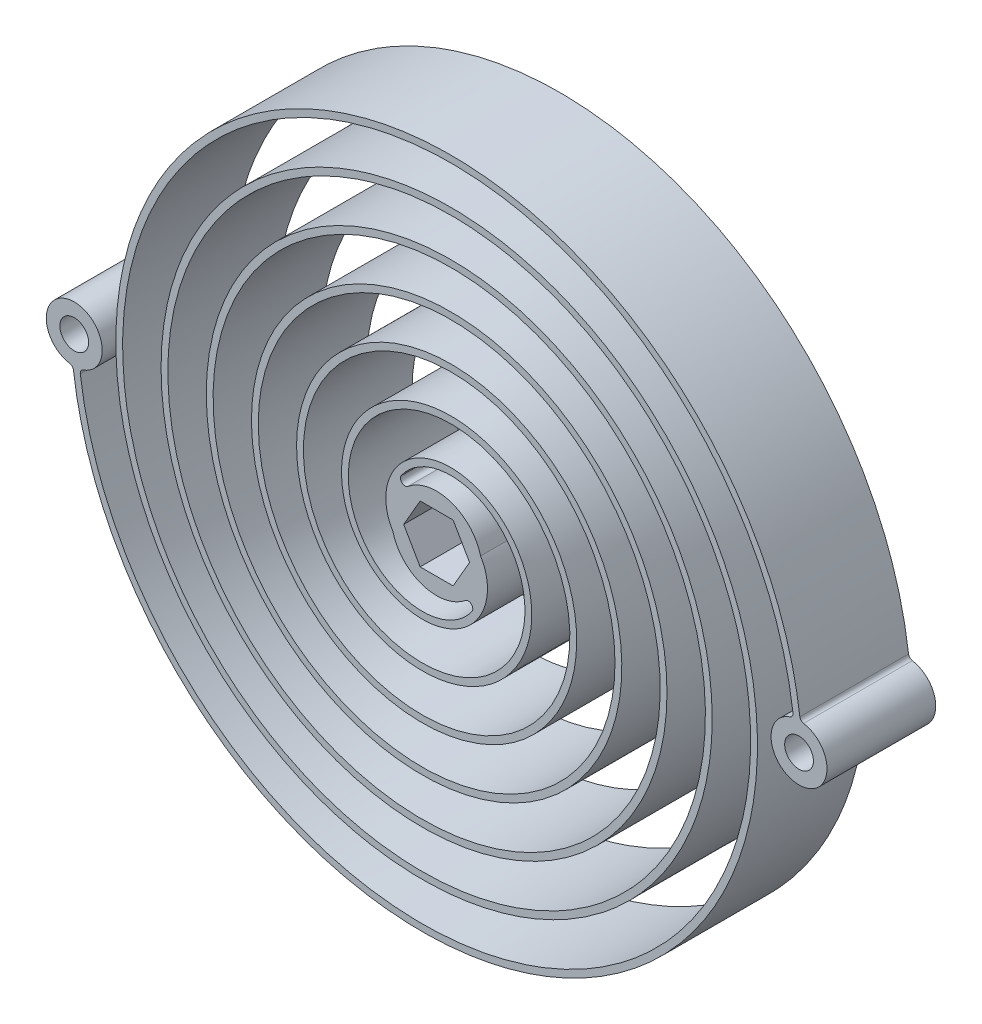
SolidWorks part; units mm, degrees
material "ASTM A36 Steel"
ref_plane "Front Plane" through (0, 0, 0) normal (0, 0, 1) x (1, 0, 0)
ref_plane "Top Plane" through (0, 0, 0) normal (0, 1, 0) x (1, 0, 0)
ref_plane "Right Plane" through (0, 0, 0) normal (1, 0, 0) x (0, 0, -1)
sketch "Base Spring Geometry" plane through (0, 0, 0) normal (0, 0, 1) x (1, 0, 0)
  line L1 (1.8187, 3.15) -> (-1.8187, 3.15)
  line L2 (-1.8187, 3.15) -> (-3.6373, 0)
  line L3 (-3.6373, 0) -> (-1.8187, -3.15)
  line L4 (-1.8187, -3.15) -> (1.8187, -3.15)
  line L5 (1.8187, -3.15) -> (3.6373, 0)
  line L6 (3.6373, 0) -> (1.8187, 3.15)
  circle A1 centre (0, 0) radius 40 construction
  circle A3 centre (0, 0) radius 5
  circle A4 centre (0, 0) radius 3.15 construction
  point P26 (0, 0)
  dimension "D1" = 6.3
sketch "Spring Spiral" plane through (0, 0, 0) normal (0, 0, 1) x (1, 0, 0)
  circle A0 centre (0, 0) radius 5
  dimension "D1" = 10
curve "Spring Arm Spiral"
sketch "Sketch12" plane through (0, 0, 0) normal (0, 0, 1) x (1, 0, 0)
  line L1 (3.6373, 0) -> (1.8187, 3.15)
  line L2 (1.8187, 3.15) -> (-1.8187, 3.15)
  line L3 (-1.8187, 3.15) -> (-3.6373, 0)
  line L4 (-3.6373, 0) -> (-1.8187, -3.15)
  line L5 (-1.8187, -3.15) -> (1.8187, -3.15)
  line L6 (1.8187, -3.15) -> (3.6373, 0)
  circle A1 centre (0, 0) radius 5
  circle A2 centre (0, 0) radius 5 construction
  circle A3 centre (0, 0) radius 3.15 construction
  point P5 (3.6373, 0)
extrude "Boss-Extrude2" add sketch "Sketch12" along normal blind 12
sketch "Sketch11" plane through (0, 0, 0) normal (0, 0, 1) x (1, 0, 0)
  arc A0 (4.8487, -1.2209) -> (4.8501, 1.2153) centre (0, 0) ccw
  circle A2 centre (0, 0) radius 5 construction
  circle A6 centre (-40, 0) radius 1.5875
  circle A7 centre (0, 0) radius 40 construction
  arc A8 (-39.3865, -3.0259) -> (-40.1348, -3.0846) centre (-40, 0) ccw
  spline S2 degree 3 poles (737.1809, -1858.5171) (-139.9817, 13.4916) (6.25, 19.9602) (4.809, -2.4575) (4.6525, -3.0957) (4.0874, -4.3221) (3.6775, -4.9127) (2.6256, -5.9433) (1.9815, -6.385) (0.521, -7.0272) (-0.2978, -7.2284) (-2.0136, -7.3241) (-2.9131, -7.2183) (-4.6721, -6.6722) (-5.5338, -6.2309) (-7.0911, -5.032) (-7.7882, -4.2727) (-8.8994, -2.5037) (-9.3144, -1.4919) (-9.7717, 0.6732) (-9.8141, 1.8288) (-9.4796, 4.1416) (-9.1019, 5.301) (-7.9336, 7.467) (-7.1417, 8.4754) (-5.2081, 10.1914) (-4.0646, 10.9001) (-1.5445, 11.8953) (-0.1658, 12.1823) (2.6671, 12.2586) (4.1232, 12.0476) (6.9297, 11.1119) (8.2818, 10.3862) (10.6978, 8.4714) (11.7632, 7.2808) (13.4469, 4.5509) (14.066, 3.0097) (14.7442, -0.2525) (14.8035, -1.9756) (14.3129, -5.3972) (13.7626, -7.0977) (12.0786, -10.2585) (10.9438, -11.7202) (8.193, -14.2038) (6.5754, -15.2266) (3.0289, -16.6749) (1.0982, -17.1008) (-2.8541, -17.2637) (-4.8775, -17.0005) (-8.7695, -15.7747) (-10.6397, -14.8114) (-13.9842, -12.2621) (-15.4597, -10.6749) (-17.8092, -7.0375) (-18.6837, -4.9857) (-19.689, -0.6455) (-19.8198, 1.6445) (-19.2799, 6.1926) (-18.6087, 8.4522) (-16.5039, 12.6601) (-15.0693, 14.6096) (-11.5732, 17.942) (-9.5104, 19.3257) (-4.9781, 21.3279) (-2.5071, 21.9467) (2.5601, 22.3051) (5.1577, 22.0445) (10.1674, 20.6329) (12.5807, 19.4811) (16.919, 16.3849) (18.8448, 14.4393) (21.9509, 9.9551) (23.1316, 7.4153) (24.57, 2.024) (24.8277, -0.8287) (24.3475, -6.5134) (23.6092, -9.3466) (21.1829, -14.6477) (19.4943, -17.1166) (15.3312, -21.3748) (12.8561, -23.1644) (8.7533, -25.1557) (7.3211, -25.7047) (4.3686, -26.552) (2.848, -26.8502) (-0.2371, -27.1818) (-1.802, -27.2151) (-4.9295, -27.0105) (-6.4924, -26.7726) (-9.5688, -26.0273) (-11.0827, -25.5199) (-14.0144, -24.2455) (-15.4325, -23.4785) (-18.1284, -21.7031) (-19.4064, -20.6945) (-21.7806, -18.4616) (-22.8771, -17.2371) (-24.8521, -14.6052) (-25.7308, -13.1975) (-27.2394, -10.2381) (-27.8696, -8.6861) (-28.8577, -5.4819) (-29.2158, -3.8295) (-29.6439, -0.4723) (-29.714, 1.2327) (-29.5588, 4.6449) (-29.3335, 6.3522) (-28.589, 9.7178) (-28.0696, 11.3762) (-26.7473, 14.5932) (-25.9441, 16.152) (-24.0732, 19.1212) (-23.0053, 20.5319) (-20.6322, 23.1597) (-19.3268, 24.377) (-16.5138, 26.5785) (-15.006, 27.5627) (-11.8297, 29.2642) (-10.161, 29.9817) (-6.7105, 31.1235) (-4.9283, 31.548) (-1.3021, 32.0862) (0.5421, 32.1999) (4.2382, 32.1079) (6.0902, 31.9022) (9.7465, 31.1722) (11.551, 30.6477) (15.0572, 29.2906) (16.7593, 28.4579) (20.0079, 26.5039) (21.5548, 25.3826) (24.4443, 22.8805) (25.7872, 21.4995) (28.225, 18.515) (29.3202, 16.9114) (31.2261, 13.5261) (32.0368, 11.7442) (33.345, 8.053) (33.8424, 6.1434) (34.5041, 2.2518) (34.6683, 0.2696) (34.6534, -3.7092) (34.4743, -5.7059) (33.7725, -9.654) (33.2499, -11.6057) (31.8715, -15.4047) (31.0157, -17.2522) (28.9914, -20.7861) (27.8228, -22.4727) (25.2031, -25.6317) (23.7518, -27.1043) (20.606, -29.7882) (18.9112, -30.9996) (15.3252, -33.121) (13.4338, -34.031) (9.5081, -35.5179) (7.4737, -36.0948) (3.3207, -36.8933) (1.2019, -37.1148) (-3.0578, -37.1908) (-5.1989, -37.0452) (-9.4396, -36.3856) (-11.5394, -35.8717) (-15.6341, -34.4857) (-17.6292, -33.6135) (-21.4535, -31.5317) (-23.2829, -30.322) (-26.7188, -27.5966) (-28.3254, -26.0807) (-31.2646, -22.7839) (-32.5974, -21.0027) (-34.9451, -17.2246) (-35.9602, -15.2275) (-37.6381, -11.0742) (-38.3009, -8.9178) (-57.4366, 80.0549) (215.829, 242.2912) (1201.7751, -1542.9243) knots -0.540256 -0.540256 -0.540256 -0.540256 0.015625 0.015625 0.03125 0.03125 0.046875 0.046875 0.0625 0.0625 0.078125 0.078125 0.09375 0.09375 0.109375 0.109375 0.125 0.125 0.140625 0.140625 0.15625 0.15625 0.171875 0.171875 0.1875 0.1875 0.203125 0.203125 0.21875 0.21875 0.234375 0.234375 0.25 0.25 0.265625 0.265625 0.28125 0.28125 0.296875 0.296875 0.3125 0.3125 0.328125 0.328125 0.34375 0.34375 0.359375 0.359375 0.375 0.375 0.390625 0.390625 0.40625 0.40625 0.421875 0.421875 0.4375 0.4375 0.453125 0.453125 0.46875 0.46875 0.484375 0.484375 0.5 0.5 0.515625 0.515625 0.53125 0.53125 0.546875 0.546875 0.5625 0.5625 0.578125 0.578125 0.59375 0.59375 0.609375 0.609375 0.625 0.625 0.632812 0.632812 0.640625 0.640625 0.648437 0.648437 0.65625 0.65625 0.664062 0.664062 0.671875 0.671875 0.679687 0.679687 0.6875 0.6875 0.695312 0.695312 0.703125 0.703125 0.710937 0.710937 0.71875 0.71875 0.726562 0.726562 0.734375 0.734375 0.742187 0.742187 0.75 0.75 0.757812 0.757812 0.765625 0.765625 0.773438 0.773438 0.78125 0.78125 0.789062 0.789062 0.796875 0.796875 0.804688 0.804688 0.8125 0.8125 0.820312 0.820312 0.828125 0.828125 0.835938 0.835938 0.84375 0.84375 0.851562 0.851562 0.859375 0.859375 0.867188 0.867188 0.875 0.875 0.882812 0.882812 0.890625 0.890625 0.898438 0.898438 0.90625 0.90625 0.914062 0.914062 0.921875 0.921875 0.929688 0.929688 0.9375 0.9375 0.945312 0.945312 0.953125 0.953125 0.960938 0.960938 0.96875 0.96875 0.976562 0.976562 0.984375 0.984375 0.992188 0.992188 1.299623 1.299623 1.299623 1.299623 only from (4.6427, -0.1137) to (-29.6436, 0.4118)
  spline S3 degree 3 poles (4.8487, -1.2209) (4.8617, -1.425) (4.862, -1.6335) (4.809, -2.4575) (4.6525, -3.0957) (4.0874, -4.3221) (3.6775, -4.9127) (2.6256, -5.9433) (1.9815, -6.385) (0.521, -7.0272) (-0.2978, -7.2284) (-2.0136, -7.3241) (-2.9131, -7.2183) (-4.6721, -6.6722) (-5.5338, -6.2309) (-7.0911, -5.032) (-7.7882, -4.2727) (-8.8994, -2.5037) (-9.3144, -1.4919) (-9.7717, 0.6732) (-9.8141, 1.8288) (-9.4796, 4.1416) (-9.1019, 5.301) (-7.9336, 7.467) (-7.1417, 8.4754) (-5.2081, 10.1914) (-4.0646, 10.9001) (-1.5445, 11.8953) (-0.1658, 12.1823) (2.6671, 12.2586) (4.1232, 12.0476) (6.9297, 11.1119) (8.2818, 10.3862) (10.6978, 8.4714) (11.7632, 7.2808) (13.4469, 4.5509) (14.066, 3.0097) (14.7442, -0.2525) (14.8035, -1.9756) (14.3129, -5.3972) (13.7626, -7.0977) (12.0786, -10.2585) (10.9438, -11.7202) (8.193, -14.2038) (6.5754, -15.2266) (3.0289, -16.6749) (1.0982, -17.1008) (-2.8541, -17.2637) (-4.8775, -17.0005) (-8.7695, -15.7747) (-10.6397, -14.8114) (-13.9842, -12.2621) (-15.4597, -10.6749) (-17.8092, -7.0375) (-18.6837, -4.9857) (-19.689, -0.6455) (-19.8198, 1.6445) (-19.2799, 6.1926) (-18.6087, 8.4522) (-16.5039, 12.6601) (-15.0693, 14.6096) (-11.5732, 17.942) (-9.5104, 19.3257) (-4.9781, 21.3279) (-2.5071, 21.9467) (2.5601, 22.3051) (5.1577, 22.0445) (10.1674, 20.6329) (12.5807, 19.4811) (16.919, 16.3849) (18.8448, 14.4393) (21.9509, 9.9551) (23.1316, 7.4153) (24.57, 2.024) (24.8277, -0.8287) (24.3475, -6.5134) (23.6092, -9.3466) (21.1829, -14.6477) (19.4943, -17.1166) (15.3312, -21.3748) (12.8561, -23.1644) (8.7533, -25.1557) (7.3211, -25.7047) (4.3686, -26.552) (2.848, -26.8502) (-0.2371, -27.1818) (-1.802, -27.2151) (-4.9295, -27.0105) (-6.4924, -26.7726) (-9.5688, -26.0273) (-11.0827, -25.5199) (-14.0144, -24.2455) (-15.4325, -23.4785) (-18.1284, -21.7031) (-19.4064, -20.6945) (-21.7806, -18.4616) (-22.8771, -17.2371) (-24.8521, -14.6052) (-25.7308, -13.1975) (-27.2394, -10.2381) (-27.8696, -8.6861) (-28.8577, -5.4819) (-29.2158, -3.8295) (-29.6439, -0.4723) (-29.714, 1.2327) (-29.5588, 4.6449) (-29.3335, 6.3522) (-28.589, 9.7178) (-28.0696, 11.3762) (-26.7473, 14.5932) (-25.9441, 16.152) (-24.0732, 19.1212) (-23.0053, 20.5319) (-20.6322, 23.1597) (-19.3268, 24.377) (-16.5138, 26.5785) (-15.006, 27.5627) (-11.8297, 29.2642) (-10.161, 29.9817) (-6.7105, 31.1235) (-4.9283, 31.548) (-1.3021, 32.0862) (0.5421, 32.1999) (4.2382, 32.1079) (6.0902, 31.9022) (9.7465, 31.1722) (11.551, 30.6477) (15.0572, 29.2906) (16.7593, 28.4579) (20.0079, 26.5039) (21.5548, 25.3826) (24.4443, 22.8805) (25.7872, 21.4995) (28.225, 18.515) (29.3202, 16.9114) (31.2261, 13.5261) (32.0368, 11.7442) (33.345, 8.053) (33.8424, 6.1434) (34.5041, 2.2518) (34.6683, 0.2696) (34.6534, -3.7092) (34.4743, -5.7059) (33.7725, -9.654) (33.2499, -11.6057) (31.8715, -15.4047) (31.0157, -17.2522) (28.9914, -20.7861) (27.8228, -22.4727) (25.2031, -25.6317) (23.7518, -27.1043) (20.606, -29.7882) (18.9112, -30.9996) (15.3252, -33.121) (13.4338, -34.031) (9.5081, -35.5179) (7.4737, -36.0948) (3.3207, -36.8933) (1.2019, -37.1148) (-3.0578, -37.1908) (-5.1989, -37.0452) (-9.4396, -36.3856) (-11.5394, -35.8717) (-15.6341, -34.4857) (-17.6292, -33.6135) (-21.4535, -31.5317) (-23.2829, -30.322) (-26.7188, -27.5966) (-28.3254, -26.0807) (-31.2646, -22.7839) (-32.5974, -21.0027) (-34.9451, -17.2246) (-35.9602, -15.2275) (-37.6381, -11.0742) (-38.3009, -8.9178) (-39.0366, -5.4969) (-39.2408, -4.266) (-39.3865, -3.0259) knots 0.010243 0.010243 0.010243 0.010243 0.015625 0.015625 0.03125 0.03125 0.046875 0.046875 0.0625 0.0625 0.078125 0.078125 0.09375 0.09375 0.109375 0.109375 0.125 0.125 0.140625 0.140625 0.15625 0.15625 0.171875 0.171875 0.1875 0.1875 0.203125 0.203125 0.21875 0.21875 0.234375 0.234375 0.25 0.25 0.265625 0.265625 0.28125 0.28125 0.296875 0.296875 0.3125 0.3125 0.328125 0.328125 0.34375 0.34375 0.359375 0.359375 0.375 0.375 0.390625 0.390625 0.40625 0.40625 0.421875 0.421875 0.4375 0.4375 0.453125 0.453125 0.46875 0.46875 0.484375 0.484375 0.5 0.5 0.515625 0.515625 0.53125 0.53125 0.546875 0.546875 0.5625 0.5625 0.578125 0.578125 0.59375 0.59375 0.609375 0.609375 0.625 0.625 0.632812 0.632812 0.640625 0.640625 0.648437 0.648437 0.65625 0.65625 0.664062 0.664062 0.671875 0.671875 0.679687 0.679687 0.6875 0.6875 0.695312 0.695312 0.703125 0.703125 0.710937 0.710937 0.71875 0.71875 0.726562 0.726562 0.734375 0.734375 0.742187 0.742187 0.75 0.75 0.757812 0.757812 0.765625 0.765625 0.773438 0.773438 0.78125 0.78125 0.789062 0.789062 0.796875 0.796875 0.804688 0.804688 0.8125 0.8125 0.820312 0.820312 0.828125 0.828125 0.835938 0.835938 0.84375 0.84375 0.851562 0.851562 0.859375 0.859375 0.867188 0.867188 0.875 0.875 0.882812 0.882812 0.890625 0.890625 0.898438 0.898438 0.90625 0.90625 0.914062 0.914062 0.921875 0.921875 0.929688 0.929688 0.9375 0.9375 0.945312 0.945312 0.953125 0.953125 0.960938 0.960938 0.96875 0.96875 0.976562 0.976562 0.984375 0.984375 0.992188 0.992188 0.996496 0.996496 0.996496 0.996496
  spline S4 degree 3 poles (659.5761, -1886.1511) (-163.6872, 17.8098) (7.2283, 23.4878) (5.5515, -2.599) (5.3723, -3.3256) (4.7299, -4.7199) (4.2678, -5.3843) (3.085, -6.5432) (2.3666, -7.035) (0.7397, -7.7504) (-0.1658, -7.9722) (-2.0622, -8.0779) (-3.0495, -7.9612) (-4.9803, -7.3619) (-5.9204, -6.8799) (-7.6196, -5.5716) (-8.3758, -4.7472) (-9.582, -2.827) (-10.0298, -1.734) (-10.5239, 0.6053) (-10.5691, 1.8483) (-10.2091, 4.3369) (-9.8041, 5.579) (-8.5517, 7.901) (-7.7056, 8.9777) (-5.6397, 10.811) (-4.4223, 11.5652) (-1.7379, 12.6253) (-0.2741, 12.9297) (2.735, 13.0107) (4.2769, 12.7869) (7.2504, 11.7955) (8.6787, 11.0286) (11.2326, 9.0046) (12.3554, 7.7493) (14.1314, 4.8698) (14.7824, 3.2484) (15.4964, -0.1858) (15.5583, -1.9952) (15.0429, -5.5905) (14.4657, -7.373) (12.6993, -10.6885) (11.5115, -12.2182) (8.6306, -14.8192) (6.94, -15.8878) (3.2314, -17.4023) (1.2165, -17.8465) (-2.9107, -18.0167) (-5.0194, -17.7422) (-9.0782, -16.4638) (-11.0248, -15.4608) (-14.5084, -12.8055) (-16.0423, -11.1552) (-18.4866, -7.371) (-19.3947, -5.24) (-20.4394, -0.7296) (-20.5748, 1.6462) (-20.0143, 6.3677) (-19.3185, 8.7096) (-17.1356, 13.0736) (-15.6499, 15.0923) (-12.0275, 18.5451) (-9.8933, 19.9765) (-5.2014, 22.0492) (-2.647, 22.6887) (2.5941, 23.0594) (5.2772, 22.7901) (10.4548, 21.3311) (12.9455, 20.1422) (17.4256, 16.9447) (19.4117, 14.938) (22.617, 10.3106) (23.8338, 7.6928) (25.3171, 2.1331) (25.5824, -0.8051) (25.0875, -6.6634) (24.3274, -9.5795) (21.8287, -15.039) (20.0914, -17.5787) (15.8066, -21.9613) (13.2613, -23.8014) (9.0419, -25.8493) (7.5695, -26.4137) (4.5339, -27.2848) (2.9711, -27.5913) (-0.1999, -27.9321) (-1.8078, -27.9663) (-5.0215, -27.7561) (-6.627, -27.5117) (-9.7874, -26.7461) (-11.342, -26.2249) (-14.353, -24.9161) (-15.809, -24.1286) (-18.577, -22.3057) (-19.8887, -21.2704) (-22.3259, -18.9784) (-23.4511, -17.7218) (-25.4779, -15.0208) (-26.3793, -13.5766) (-27.9272, -10.5402) (-28.5736, -8.9484) (-29.5872, -5.6616) (-29.9543, -3.9672) (-30.3934, -0.5243) (-30.4652, 1.2237) (-30.3061, 4.7221) (-30.0752, 6.4721) (-29.3119, 9.9219) (-28.7797, 11.6214) (-27.4245, 14.9183) (-26.6017, 16.5153) (-24.6848, 19.5576) (-23.5909, 21.0025) (-21.1599, 23.6944) (-19.8231, 24.9411) (-16.9421, 27.1957) (-15.3982, 28.2034) (-12.1458, 29.9457) (-10.4376, 30.6801) (-6.9051, 31.8491) (-5.0811, 32.2835) (-1.3695, 32.8344) (0.5176, 32.9507) (4.3, 32.8566) (6.1947, 32.6462) (9.9357, 31.8992) (11.7814, 31.3627) (15.3682, 29.9745) (17.1088, 29.1228) (20.4315, 27.1244) (22.0132, 25.9779) (24.9679, 23.4192) (26.3407, 22.0073) (28.8332, 18.9561) (29.9526, 17.3169) (31.9008, 13.8564) (32.7293, 12.0354) (34.0663, 8.2629) (34.5746, 6.3117) (35.2507, 2.335) (35.4185, 0.3099) (35.4033, -3.7551) (35.2202, -5.7946) (34.5034, -9.8277) (33.9696, -11.8209) (32.5618, -15.7011) (31.6879, -17.5876) (29.6207, -21.1963) (28.4276, -22.9182) (25.7529, -26.1436) (24.2714, -27.6469) (21.0599, -30.3868) (19.3302, -31.6232) (15.6699, -33.7884) (13.7397, -34.7171) (9.7335, -36.2345) (7.6577, -36.8232) (3.4199, -37.6379) (1.2584, -37.864) (-3.0875, -37.9414) (-5.2715, -37.7929) (-9.5974, -37.1201) (-11.739, -36.596) (-15.9154, -35.1823) (-17.9499, -34.2928) (-21.85, -32.1698) (-23.7152, -30.9364) (-27.2187, -28.1574) (-28.8565, -26.612) (-31.8532, -23.2508) (-33.2116, -21.4352) (-35.6049, -17.5839) (-36.6395, -15.5485) (-38.3496, -11.3152) (-39.025, -9.1177) (-58.5091, 81.4745) (219.5603, 245.8676) (1214.263, -1531.227) knots -0.545857 -0.545857 -0.545857 -0.545857 0.015625 0.015625 0.03125 0.03125 0.046875 0.046875 0.0625 0.0625 0.078125 0.078125 0.09375 0.09375 0.109375 0.109375 0.125 0.125 0.140625 0.140625 0.15625 0.15625 0.171875 0.171875 0.1875 0.1875 0.203125 0.203125 0.21875 0.21875 0.234375 0.234375 0.25 0.25 0.265625 0.265625 0.28125 0.28125 0.296875 0.296875 0.3125 0.3125 0.328125 0.328125 0.34375 0.34375 0.359375 0.359375 0.375 0.375 0.390625 0.390625 0.40625 0.40625 0.421875 0.421875 0.4375 0.4375 0.453125 0.453125 0.46875 0.46875 0.484375 0.484375 0.5 0.5 0.515625 0.515625 0.53125 0.53125 0.546875 0.546875 0.5625 0.5625 0.578125 0.578125 0.59375 0.59375 0.609375 0.609375 0.625 0.625 0.632812 0.632812 0.640625 0.640625 0.648438 0.648438 0.65625 0.65625 0.664062 0.664062 0.671875 0.671875 0.679688 0.679688 0.6875 0.6875 0.695312 0.695312 0.703125 0.703125 0.710938 0.710938 0.71875 0.71875 0.726562 0.726562 0.734375 0.734375 0.742188 0.742188 0.75 0.75 0.757812 0.757812 0.765625 0.765625 0.773438 0.773438 0.78125 0.78125 0.789062 0.789062 0.796875 0.796875 0.804688 0.804688 0.8125 0.8125 0.820312 0.820312 0.828125 0.828125 0.835938 0.835938 0.84375 0.84375 0.851562 0.851562 0.859375 0.859375 0.867188 0.867188 0.875 0.875 0.882812 0.882812 0.890625 0.890625 0.898438 0.898438 0.90625 0.90625 0.914062 0.914062 0.921875 0.921875 0.929688 0.929688 0.9375 0.9375 0.945312 0.945312 0.953125 0.953125 0.960938 0.960938 0.96875 0.96875 0.976562 0.976562 0.984375 0.984375 0.992188 0.992188 1.299339 1.299339 1.299339 1.299339 only from (5.3573, 0.1137) to (-30.3931, 0.382)
  spline S5 degree 3 poles (4.8501, 1.2153) (5.3853, 0.3632) (5.6714, -0.7323) (5.5515, -2.599) (5.3723, -3.3256) (4.7299, -4.7199) (4.2678, -5.3843) (3.085, -6.5432) (2.3666, -7.035) (0.7397, -7.7504) (-0.1658, -7.9722) (-2.0622, -8.0779) (-3.0495, -7.9612) (-4.9803, -7.3619) (-5.9204, -6.8799) (-7.6196, -5.5716) (-8.3758, -4.7472) (-9.582, -2.827) (-10.0298, -1.734) (-10.5239, 0.6053) (-10.5691, 1.8483) (-10.2091, 4.3369) (-9.8041, 5.579) (-8.5517, 7.901) (-7.7056, 8.9777) (-5.6397, 10.811) (-4.4223, 11.5652) (-1.7379, 12.6253) (-0.2741, 12.9297) (2.735, 13.0107) (4.2769, 12.7869) (7.2504, 11.7955) (8.6787, 11.0286) (11.2326, 9.0046) (12.3554, 7.7493) (14.1314, 4.8698) (14.7824, 3.2484) (15.4964, -0.1858) (15.5583, -1.9952) (15.0429, -5.5905) (14.4657, -7.373) (12.6993, -10.6885) (11.5115, -12.2182) (8.6306, -14.8192) (6.94, -15.8878) (3.2314, -17.4023) (1.2165, -17.8465) (-2.9107, -18.0167) (-5.0194, -17.7422) (-9.0782, -16.4638) (-11.0248, -15.4608) (-14.5084, -12.8055) (-16.0423, -11.1552) (-18.4866, -7.371) (-19.3947, -5.24) (-20.4394, -0.7296) (-20.5748, 1.6462) (-20.0143, 6.3677) (-19.3185, 8.7096) (-17.1356, 13.0736) (-15.6499, 15.0923) (-12.0275, 18.5451) (-9.8933, 19.9765) (-5.2014, 22.0492) (-2.647, 22.6887) (2.5941, 23.0594) (5.2772, 22.7901) (10.4548, 21.3311) (12.9455, 20.1422) (17.4256, 16.9447) (19.4117, 14.938) (22.617, 10.3106) (23.8338, 7.6928) (25.3171, 2.1331) (25.5824, -0.8051) (25.0875, -6.6634) (24.3274, -9.5795) (21.8287, -15.039) (20.0914, -17.5787) (15.8066, -21.9613) (13.2613, -23.8014) (9.0419, -25.8493) (7.5695, -26.4137) (4.5339, -27.2848) (2.9711, -27.5913) (-0.1999, -27.9321) (-1.8078, -27.9663) (-5.0215, -27.7561) (-6.627, -27.5117) (-9.7874, -26.7461) (-11.342, -26.2249) (-14.353, -24.9161) (-15.809, -24.1286) (-18.577, -22.3057) (-19.8887, -21.2704) (-22.3259, -18.9784) (-23.4511, -17.7218) (-25.4779, -15.0208) (-26.3793, -13.5766) (-27.9272, -10.5402) (-28.5736, -8.9484) (-29.5872, -5.6616) (-29.9543, -3.9672) (-30.3934, -0.5243) (-30.4652, 1.2237) (-30.3061, 4.7221) (-30.0752, 6.4721) (-29.3119, 9.9219) (-28.7797, 11.6214) (-27.4245, 14.9183) (-26.6017, 16.5153) (-24.6848, 19.5576) (-23.5909, 21.0025) (-21.1599, 23.6944) (-19.8231, 24.9411) (-16.9421, 27.1957) (-15.3982, 28.2034) (-12.1458, 29.9457) (-10.4376, 30.6801) (-6.9051, 31.8491) (-5.0811, 32.2835) (-1.3695, 32.8344) (0.5176, 32.9507) (4.3, 32.8566) (6.1947, 32.6462) (9.9357, 31.8992) (11.7814, 31.3627) (15.3682, 29.9745) (17.1088, 29.1228) (20.4315, 27.1244) (22.0132, 25.9779) (24.9679, 23.4192) (26.3407, 22.0073) (28.8332, 18.9561) (29.9526, 17.3169) (31.9008, 13.8564) (32.7293, 12.0354) (34.0663, 8.2629) (34.5746, 6.3117) (35.2507, 2.335) (35.4185, 0.3099) (35.4033, -3.7551) (35.2202, -5.7946) (34.5034, -9.8277) (33.9696, -11.8209) (32.5618, -15.7011) (31.6879, -17.5876) (29.6207, -21.1963) (28.4276, -22.9182) (25.7529, -26.1436) (24.2714, -27.6469) (21.0599, -30.3868) (19.3302, -31.6232) (15.6699, -33.7884) (13.7397, -34.7171) (9.7335, -36.2345) (7.6577, -36.8232) (3.4199, -37.6379) (1.2584, -37.864) (-3.0875, -37.9414) (-5.2715, -37.7929) (-9.5974, -37.1201) (-11.739, -36.596) (-15.9154, -35.1823) (-17.9499, -34.2928) (-21.85, -32.1698) (-23.7152, -30.9364) (-27.2187, -28.1574) (-28.8565, -26.612) (-31.8532, -23.2508) (-33.2116, -21.4352) (-35.6049, -17.5839) (-36.6395, -15.5485) (-38.3496, -11.3152) (-39.025, -9.1177) (-39.7769, -5.6219) (-39.9861, -4.358) (-40.1348, -3.0846) knots -0.010046 -0.010046 -0.010046 -0.010046 0.015625 0.015625 0.03125 0.03125 0.046875 0.046875 0.0625 0.0625 0.078125 0.078125 0.09375 0.09375 0.109375 0.109375 0.125 0.125 0.140625 0.140625 0.15625 0.15625 0.171875 0.171875 0.1875 0.1875 0.203125 0.203125 0.21875 0.21875 0.234375 0.234375 0.25 0.25 0.265625 0.265625 0.28125 0.28125 0.296875 0.296875 0.3125 0.3125 0.328125 0.328125 0.34375 0.34375 0.359375 0.359375 0.375 0.375 0.390625 0.390625 0.40625 0.40625 0.421875 0.421875 0.4375 0.4375 0.453125 0.453125 0.46875 0.46875 0.484375 0.484375 0.5 0.5 0.515625 0.515625 0.53125 0.53125 0.546875 0.546875 0.5625 0.5625 0.578125 0.578125 0.59375 0.59375 0.609375 0.609375 0.625 0.625 0.632812 0.632812 0.640625 0.640625 0.648438 0.648438 0.65625 0.65625 0.664062 0.664062 0.671875 0.671875 0.679688 0.679688 0.6875 0.6875 0.695312 0.695312 0.703125 0.703125 0.710938 0.710938 0.71875 0.71875 0.726562 0.726562 0.734375 0.734375 0.742188 0.742188 0.75 0.75 0.757812 0.757812 0.765625 0.765625 0.773438 0.773438 0.78125 0.78125 0.789062 0.789062 0.796875 0.796875 0.804688 0.804688 0.8125 0.8125 0.820312 0.820312 0.828125 0.828125 0.835938 0.835938 0.84375 0.84375 0.851562 0.851562 0.859375 0.859375 0.867188 0.867188 0.875 0.875 0.882812 0.882812 0.890625 0.890625 0.898438 0.898438 0.90625 0.90625 0.914062 0.914062 0.921875 0.921875 0.929688 0.929688 0.9375 0.9375 0.945312 0.945312 0.953125 0.953125 0.960938 0.960938 0.96875 0.96875 0.976562 0.976562 0.984375 0.984375 0.992188 0.992188 0.996529 0.996529 0.996529 0.996529
  point P3 (1.5416, -1.6324)
  point P4 (4.7035, -1.6961)
  point P5 (1.9383, -0.2754)
  point P6 (4.7166, 1.6594)
  point P31 (-40, 0)
  dimension "D3" = 3.175
  dimension "D4" = 1.5
  dimension "D1" = 0.375
  dimension "D2" = 0.375
extrude "Boss-Extrude1" add sketch "Sketch11" along normal blind 12
ref_axis "Axis1" through (0, 0, -61.5333) along (0, 0, 1)
pattern_circular "CirPattern1" count 2 over 360 about axis through (0, 0, -61.5333) along (0, 0, 1) of "Boss-Extrude1"
fillet "Fillet1" radius 0.5 6 edges
equation "\"Spring OD\" = 80.00mm"
equation "\"Spring ID\"= 10mm"
equation "\"t\" = 0.75"
equation "\"b\"= 12"
equation "\"D1@Spring Spiral\"=\"Spring ID\""
equation "\"n\"= 2"
equation "\"Spring ID@Base Spring Geometry\"=\"Spring ID\""
equation "\"rev\" = 3.5"
equation "\"D5@Spring Arm Spiral\"=\"rev\""
equation "\"D4@Spring Arm Spiral\"=(\"Spring OD\"-\"Spring ID\")/(2*\"rev\")"
equation "\"D1@Sketch11\"=\"t\"/2"
equation "\"D2@Sketch11\"=\"t\"/2"
equation "\"D1@Boss-Extrude1\"=\"b\""
equation "\"D1@Boss-Extrude2\"=\"b\""
equation "\"Bolt Centerline@Base Spring Geometry\"=\"Spring OD\""
